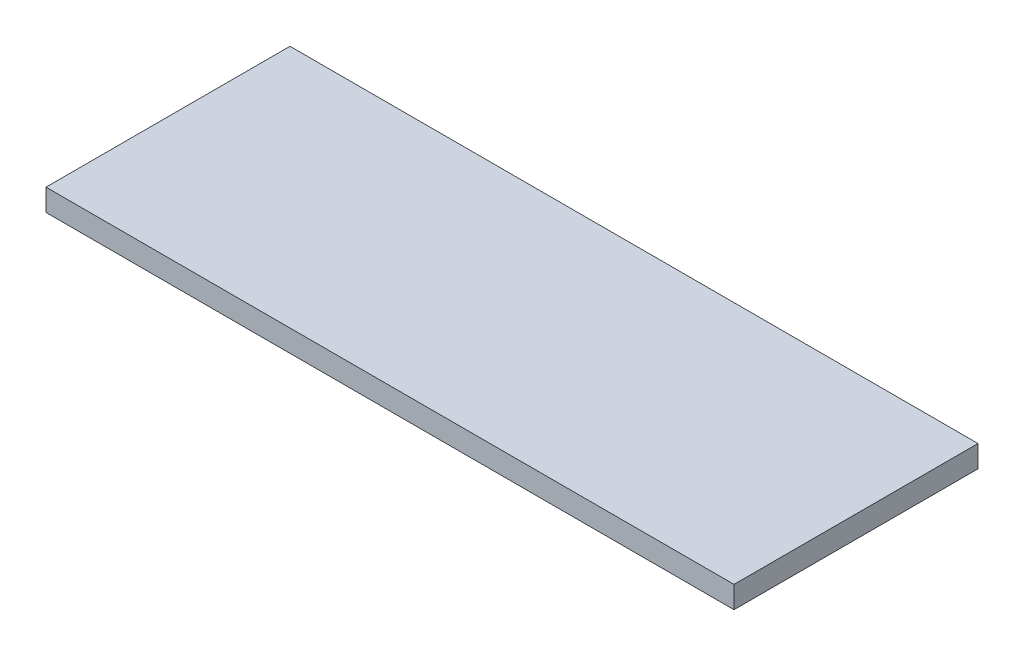
SolidWorks part; units mm, degrees
material "Sosna"
ref_plane "Płaszczyzna przednia" through (0, 0, 0) normal (0, 0, 1) x (1, 0, 0)
ref_plane "Płaszczyzna górna" through (0, 0, 0) normal (0, 1, 0) x (1, 0, 0)
ref_plane "Płaszczyzna prawa" through (0, 0, 0) normal (1, 0, 0) x (0, 0, -1)
sketch "Szkic1" plane through (0, 0, 0) normal (0, 1, 0) x (1, 0, 0)
  line L1 (0, 0) -> (-564, 0)
  line L2 (0, 0) -> (0, 200)
  line L3 (0, 200) -> (-564, 200)
  line L4 (-564, 0) -> (-564, 200)
  dimension "D1" = 200
  dimension "D2" = 564
extrude "Dodanie-wyciągnięcie1" add sketch "Szkic1" along normal blind 18
